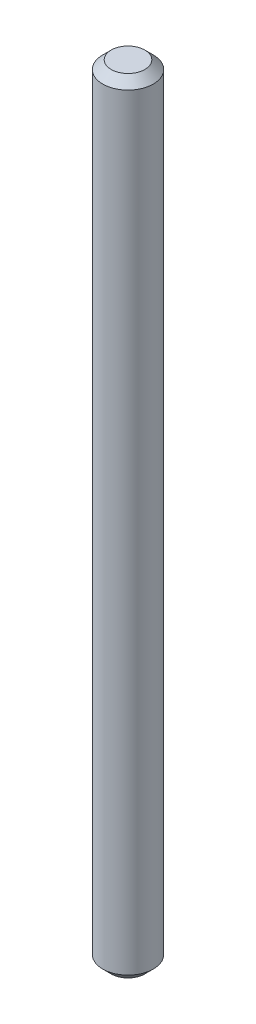
SolidWorks part; units mm, degrees
material "AISI 316 Stainless Steel Sheet (SS)"
ref_plane "Спереди" through (0, 0, 0) normal (0, 0, 1) x (1, 0, 0)
ref_plane "Сверху" through (0, 0, 0) normal (0, 1, 0) x (1, 0, 0)
ref_plane "Справа" through (0, 0, 0) normal (1, 0, 0) x (0, 0, -1)
sketch "Sketch1" plane through (0, 0, 0) normal (0, 0, 1) x (1, 0, 0)
  line L1 (0, 0) -> (3, 0)
  line L2 (0, 0) -> (0, 93)
  line L3 (0, 93) -> (3, 93)
  line L4 (3, 0) -> (3, 93)
  dimension "D1" = 93
  dimension "D2" = 3
revolve "Revolve1" add sketch "Sketch1" angle 360 about L2
chamfer "Chamfer1" distance 1 2 edges at (0, 0, -3) (0, 93, -3)
